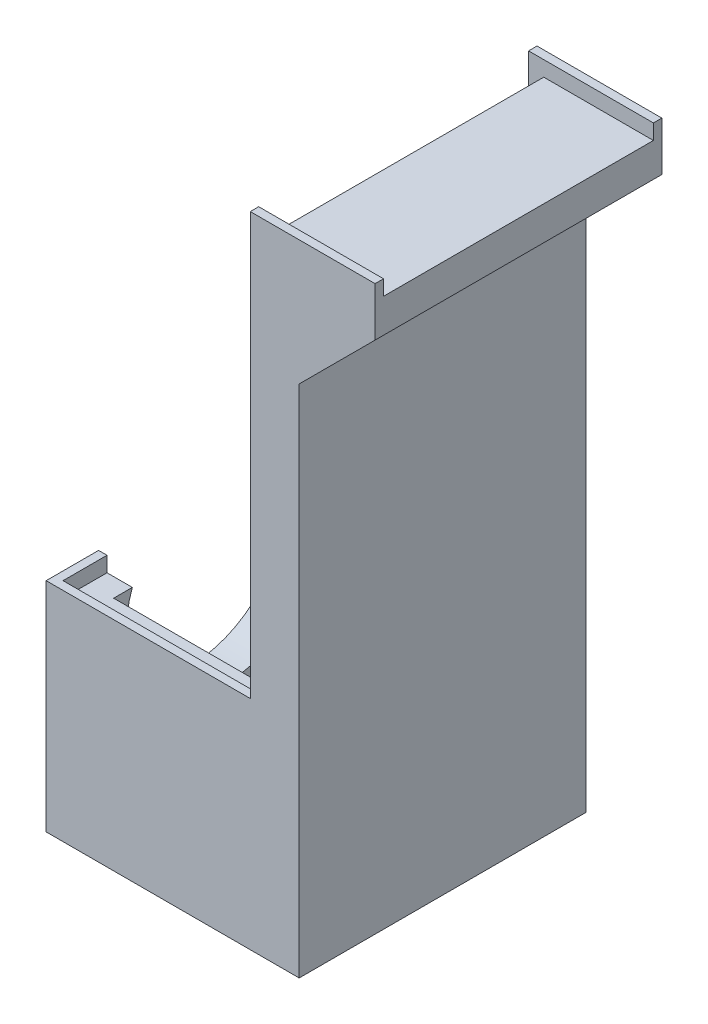
SolidWorks part; units mm, degrees
ref_plane "Front Plane" through (0, 0, 0) normal (0, 0, 1) x (1, 0, 0)
ref_plane "Top Plane" through (0, 0, 0) normal (0, 1, 0) x (1, 0, 0)
ref_plane "Right Plane" through (0, 0, 0) normal (1, 0, 0) x (0, 0, -1)
sketch "Sketch1" plane through (0, 0, 0) normal (0, 1, 0) x (1, 0, 0)
  line L1 (6.5, 8.5) -> (-6.5, 8.5)
  line L2 (6.5, 8.5) -> (6.5, -8.5)
  line L3 (6.5, -8.5) -> (-6.5, -8.5)
  line L4 (-6.5, 8.5) -> (-6.5, -8.5)
  line L5 (6.5, 8.5) -> (-6.5, -8.5) construction
  line L6 (6.5, -8.5) -> (-6.5, 8.5) construction
  point P0 (0, 0)
  dimension "D1" = 13
  dimension "D2" = 17
extrude "Boss-Extrude1" add sketch "Sketch1" along normal blind 2
sketch "Sketch2" plane through (0, 2, 0) normal (0, 1, 0) x (1, 0, 0)
  line L0 (-6.5, 8.5) -> (-6.5, -8.5)
  line L1 (-6.5, -8.5) -> (6.5, -8.5)
  line L2 (-6.5, 8.5) -> (6.5, 8.5)
  line L3 (6.5, 8.5) -> (6.5, 6.5)
  line L4 (6.5, -8.5) -> (6.5, 8.5) construction
  line L5 (6.5, 6.5) -> (-4.5, 6.5)
  line L6 (-4.5, 6.5) -> (-4.5, -6.5)
  line L7 (-4.5, -6.5) -> (6.5, -6.5)
  line L8 (6.5, -6.5) -> (6.5, -8.5)
  dimension "D1" = 2
  dimension "D2" = 2
  dimension "D3" = 2
extrude "Boss-Extrude2" add sketch "Sketch2" along normal blind 10
sketch "Sketch3" plane through (-6.5, 0, 0) normal (-1, 0, 0) x (0, 0, 1)
  line L1 (-8.5, 10) -> (8.5, 10) construction
  line L2 (-8.5, 12) -> (-8.5, 0) construction
  line L3 (8.5, 12) -> (8.5, 0) construction
  line L4 (-8.5, 12) -> (8.5, 12) construction
  circle A1 centre (0, 10) radius 5.75
  dimension "D1" = 2
  dimension "D2" = 11.5
extrude "Cut-Extrude1" cut sketch "Sketch3" against normal blind 15
sketch "Sketch4" plane through (6.5, 0, 0) normal (1, 0, 0) x (0, 0, -1)
  line L1 (8.5, 0) -> (-8.5, 0)
  line L2 (8.5, 0) -> (8.5, 37)
  line L3 (8.5, 37) -> (-8.5, 37)
  line L4 (-8.5, 0) -> (-8.5, 37)
  dimension "D1" = 17
  dimension "D2" = 37
extrude "Boss-Extrude3" add sketch "Sketch4" along normal blind 2
sketch "Sketch5" plane through (8.5, 0, 0) normal (1, 0, 0) x (0, 0, -1)
  line L0 (-8.5, 37) -> (-8.5, 0) construction
  line L1 (8.5, 37) -> (-8.5, 37)
  line L2 (8.5, 37) -> (8.5, 35)
  line L3 (8.5, 35) -> (-8.5, 35)
  line L4 (-8.5, 37) -> (-8.5, 35)
  dimension "D1" = 2
extrude "Boss-Extrude4" add sketch "Sketch5" along normal blind 4.5
sketch "Sketch6" plane through (0, 12, 0) normal (0, 1, 0) x (1, 0, 0)
  line L0 (-6, 5.391) -> (-6.5, 5.391)
  line L1 (-6.5, 5.391) -> (-4.5, 5.391) construction
  line L2 (-6.5, 5.391) -> (-6.5, 8.5)
  line L3 (-6.5, 8.5) -> (6.5, 8.5)
  line L4 (6.5, 8.5) -> (6.5, 8)
  line L5 (6.5, 8.5) -> (6.5, -8.5) construction
  line L6 (6.5, 8) -> (-6, 8)
  line L7 (-6, 8) -> (-6, 5.391)
  line L8 (0, 0) -> (-6.5, 0) construction
  line L9 (-6.5, 5.75) -> (-6.5, -5.75) construction
  line L10 (6.5, -8) -> (-6, -8)
  line L11 (6.5, -8.5) -> (6.5, -8)
  line L12 (-6.5, -8.5) -> (6.5, -8.5)
  line L13 (-6.5, -5.391) -> (-6.5, -8.5)
  line L14 (-6, -5.391) -> (-6.5, -5.391)
  line L15 (-6, -8) -> (-6, -5.391)
  dimension "D1" = 0.5
  dimension "D2" = 0.5
extrude "Boss-Extrude5" add sketch "Sketch6" along normal blind 0.9
sketch "Sketch7" plane through (6.5, 0, 0) normal (-1, 0, 0) x (0, 0, 1)
  line L0 (-8.5, 37) -> (8.5, 37) construction
  line L1 (-8.5, 12.9) -> (-8, 12.9)
  line L2 (-8.5, 12.9) -> (-8.5, 37)
  line L3 (-8.5, 37) -> (-8, 37)
  line L4 (-8, 12.9) -> (-8, 37)
  line L5 (0, 0) -> (0, 37) construction
  line L6 (8.5, 37) -> (8, 37)
  line L7 (8, 12.9) -> (8, 37)
  line L8 (8.5, 12.9) -> (8, 12.9)
  line L9 (8.5, 12.9) -> (8.5, 37)
  dimension "D1" = 0.5
extrude "Boss-Extrude6" add sketch "Sketch7" along normal blind 0.9
sketch "Sketch8" plane through (0, 37, 0) normal (0, 1, 0) x (1, 0, 0)
  line L1 (13, 8.5) -> (5.6, 8.5)
  line L2 (13, 8.5) -> (13, 8)
  line L3 (13, 8) -> (5.6, 8)
  line L4 (5.6, 8.5) -> (5.6, 8)
  line L5 (13, -8.5) -> (5.6, -8.5)
  line L6 (13, -8.5) -> (13, -8)
  line L7 (13, -8) -> (5.6, -8)
  line L8 (5.6, -8.5) -> (5.6, -8)
extrude "Boss-Extrude7" add sketch "Sketch8" along normal blind 0.9
sketch "Sketch9" plane through (0, 0, 8.5) normal (0, 0, 1) x (1, 0, 0)
  line L0 (13, 35) -> (8.5, 30.5)
  line L1 (8.5, 35) -> (8.5, 0) construction
  line L2 (8.5, 30.5) -> (8.5, 35)
  line L3 (8.5, 35) -> (13, 35)
extrude "Boss-Extrude8" add sketch "Sketch9" against normal blind 17
